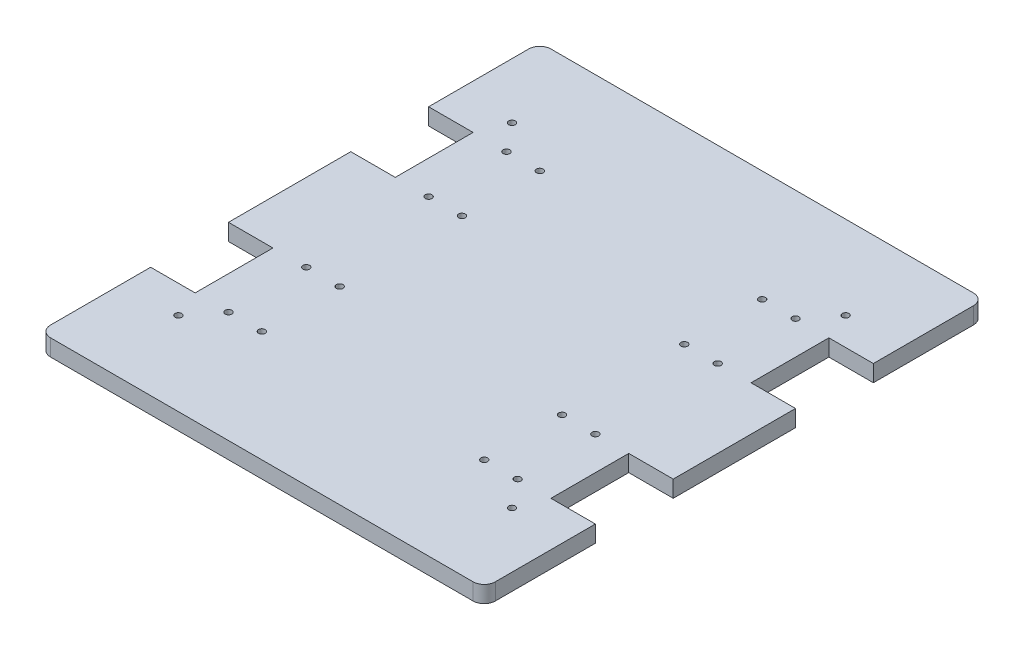
SolidWorks part; units mm, degrees
ref_plane "前基準面" through (0, 0, 0) normal (0, 0, 1) x (1, 0, 0)
ref_plane "上基準面" through (0, 0, 0) normal (0, 1, 0) x (1, 0, 0)
ref_plane "右基準面" through (0, 0, 0) normal (1, 0, 0) x (0, 0, -1)
sketch "草圖1" plane through (0, 0, 0) normal (0, 1, 0) x (1, 0, 0)
  line L0 (0, 250) -> (0, -250) construction
  line L1 (-250, 250) -> (250, 250) construction
  line L2 (-250, 250) -> (-250, -250) construction
  line L3 (-250, -250) -> (250, -250) construction
  line L4 (250, 250) -> (250, -250) construction
  line L5 (-200, 55) -> (-200, -55)
  line L6 (-250, 0) -> (250, 0) construction
  line L7 (-190, 225) -> (190, 225)
  line L8 (-200, 215) -> (-200, 125)
  line L9 (-190, -225) -> (190, -225)
  line L10 (200, 215) -> (200, 125)
  line L11 (0, -225) -> (0, 225) construction
  line L12 (-200, 0) -> (200, 0) construction
  line L13 (-200, -55) -> (-160, -55)
  line L15 (-200, -125) -> (-160, -125)
  line L16 (-160, -55) -> (-160, -125)
  line L17 (-200, 125) -> (-160, 125)
  line L19 (-200, 55) -> (-160, 55)
  line L20 (-160, 125) -> (-160, 55)
  line L21 (200, 125) -> (160, 125)
  line L23 (200, 55) -> (160, 55)
  line L24 (160, 125) -> (160, 55)
  line L25 (200, -55) -> (160, -55)
  line L27 (200, -125) -> (160, -125)
  line L28 (160, -55) -> (160, -125)
  line L29 (-200, -125) -> (-200, -215)
  line L30 (200, -125) -> (200, -215)
  line L31 (200, 55) -> (200, -55)
  arc A0 (200, 215) -> (190, 225) centre (190, 215) ccw
  arc A1 (-190, 225) -> (-200, 215) centre (-190, 215) ccw
  arc A2 (190, -225) -> (200, -215) centre (190, -215) ccw
  arc A3 (-200, -215) -> (-190, -225) centre (-190, -215) ccw
  point P0 (0, 0)
  point P8 (0, 0)
  point P11 (0, 0)
  point P35 (-200, 0)
  point P38 (200, 225)
  point P41 (-200, 225)
  point P44 (200, -225)
  point P47 (-160, 90)
  point P48 (-160, -90)
  dimension "D9" = 10
  dimension "D1" = 500
  dimension "D2" = 500
  dimension "D3" = 400
  dimension "D4" = 450
  dimension "D5" = 40
  dimension "D6" = 100
  dimension "D7" = 70
  dimension "D8" = 100
  dimension "D10" = 180
extrude "填料-伸長1" add sketch "草圖1" along normal blind 15
sketch "草圖3" plane through (0, 15, 0) normal (0, 1, 0) x (1, 0, 0)
  line L0 (0, -267.908) -> (0, 299.3088) construction
  line L1 (-314.6258, 0) -> (222.5458, 0) construction
  line L2 (85, 65) -> (145, 65) construction
  line L3 (-145, 65) -> (-85, 65) construction
  line L4 (-145, 65) -> (-145, 115) construction
  line L5 (-145, 115) -> (-85, 115) construction
  line L6 (-85, 65) -> (-85, 115) construction
  line L7 (85, 65) -> (85, 115) construction
  line L8 (-145, 90) -> (-85, 90) construction
  line L9 (-160, 125) -> (-160, 55) construction
  line L10 (85, 115) -> (145, 115) construction
  line L11 (145, 65) -> (145, 115) construction
  line L12 (85, 90) -> (145, 90) construction
  line L13 (160, 55) -> (160, 125) construction
  line L14 (-145, -115) -> (-85, -115) construction
  line L15 (-85, -65) -> (-85, -115) construction
  line L16 (-145, -65) -> (-85, -65) construction
  line L17 (-145, -65) -> (-145, -115) construction
  line L18 (85, -65) -> (85, -115) construction
  line L19 (85, -115) -> (145, -115) construction
  line L20 (145, -65) -> (145, -115) construction
  line L21 (85, -65) -> (145, -65) construction
  line L23 (-150, 150) -> (150, 150) construction
  line L24 (-150, 150) -> (-150, -150) construction
  line L25 (-150, -150) -> (150, -150) construction
  line L26 (150, 150) -> (150, -150) construction
  line L27 (0, -150) -> (0, 150) construction
  line L28 (-150, 0) -> (150, 0) construction
  line L29 (-165, 165) -> (-135, 165) construction
  line L30 (-165, 165) -> (-165, 135) construction
  line L31 (-165, 135) -> (-135, 135) construction
  line L32 (-135, 165) -> (-135, 135) construction
  line L33 (-150, 135) -> (-150, 165) construction
  line L34 (-165, 150) -> (-135, 150) construction
  line L35 (135, 165) -> (165, 165) construction
  line L36 (135, 165) -> (135, 135) construction
  line L37 (135, 135) -> (165, 135) construction
  line L38 (165, 165) -> (165, 135) construction
  line L39 (150, 135) -> (150, 165) construction
  line L40 (135, 150) -> (165, 150) construction
  line L41 (-165, -135) -> (-135, -135) construction
  line L42 (-165, -135) -> (-165, -165) construction
  line L43 (-165, -165) -> (-135, -165) construction
  line L44 (-135, -135) -> (-135, -165) construction
  line L45 (-150, -165) -> (-150, -135) construction
  line L46 (-165, -150) -> (-135, -150) construction
  line L47 (135, -135) -> (165, -135) construction
  line L48 (135, -135) -> (135, -165) construction
  line L49 (135, -165) -> (165, -165) construction
  line L50 (165, -135) -> (165, -165) construction
  line L51 (150, -165) -> (150, -135) construction
  line L52 (135, -150) -> (165, -150) construction
  circle A10 centre (-130, 125) radius 3
  circle A11 centre (-100, 125) radius 3
  circle A12 centre (-100, 55) radius 3
  circle A13 centre (-130, 55) radius 3
  circle A14 centre (100, 55) radius 3
  circle A15 centre (130, 55) radius 3
  circle A16 centre (100, 125) radius 3
  circle A17 centre (130, 125) radius 3
  circle A18 centre (100, -125) radius 3
  circle A19 centre (130, -125) radius 3
  circle A20 centre (130, -55) radius 3
  circle A21 centre (100, -55) radius 3
  circle A22 centre (-100, -55) radius 3
  circle A23 centre (-130, -55) radius 3
  circle A24 centre (-100, -125) radius 3
  circle A25 centre (-130, -125) radius 3
  circle A26 centre (-150, -150) radius 3
  circle A27 centre (150, -150) radius 3
  circle A28 centre (150, 150) radius 3
  circle A29 centre (-150, 150) radius 3
  point P0 (0, 0)
  point P34 (-160, 90)
  dimension "D3" = 300
  dimension "D4" = 30
  dimension "D11" = 6
  dimension "D14" = 6
  dimension "D5" = 6
  dimension "D6" = 50
  dimension "D7" = 60
  dimension "D8" = 15
  dimension "D9" = 15
  dimension "D10" = 60
  dimension "D12" = 10
  dimension "D13" = 15
  dimension "D15" = 15
  dimension "D2" = 300
extrude "除料-伸長1" cut sketch "草圖3" against normal blind 15
